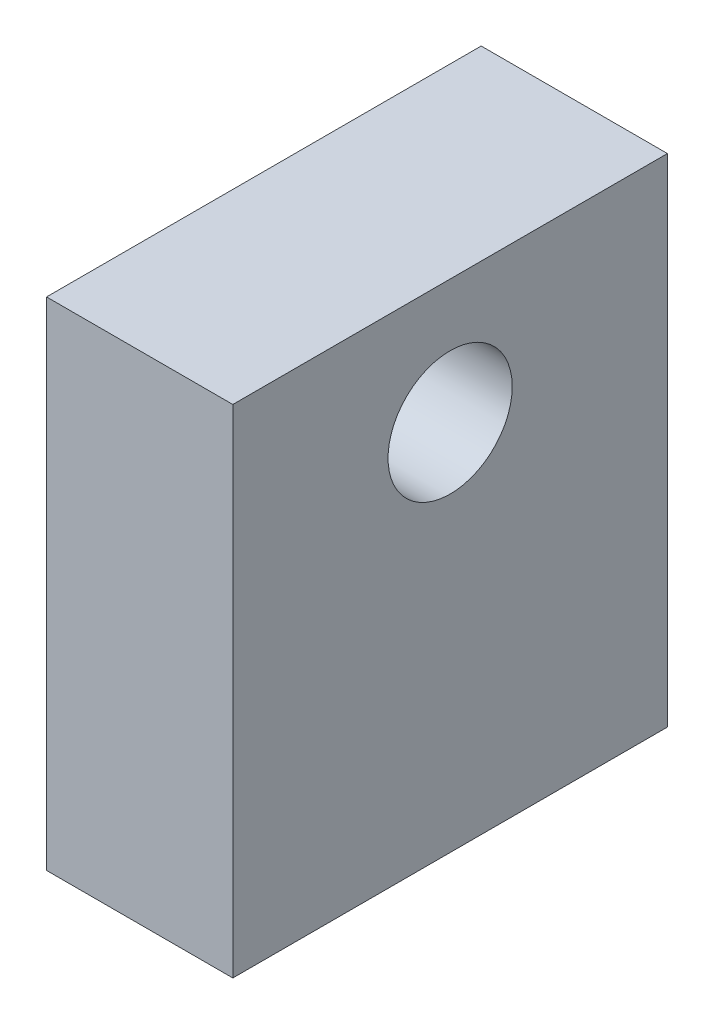
SolidWorks part; units mm, degrees
material "Pine"
ref_plane "Front Plane" through (0, 0, 0) normal (0, 0, 1) x (1, 0, 0)
ref_plane "Top Plane" through (0, 0, 0) normal (0, 1, 0) x (1, 0, 0)
ref_plane "Right Plane" through (0, 0, 0) normal (1, 0, 0) x (0, 0, -1)
sketch "Sketch1" plane through (0, 0, 0) normal (0, 1, 0) x (1, 0, 0)
  line L1 (0, 0) -> (38.1, 0)
  line L2 (0, 0) -> (0, 88.9)
  line L3 (0, 88.9) -> (38.1, 88.9)
  line L4 (38.1, 0) -> (38.1, 88.9)
  dimension "D1" = 38.1
  dimension "D2" = 88.9
extrude "Boss-Extrude1" add sketch "Sketch1" along normal blind 101.6
sketch "Sketch2" plane through (38.1, 0, 0) normal (1, 0, 0) x (0, 0, -1)
  line L0 (0, 101.6) -> (88.9, 101.6) construction
  circle A0 centre (44.45, 76.2) radius 12.7
  dimension "D1" = 25.4
  dimension "D2" = 25.4
extrude "Cut-Extrude1" cut sketch "Sketch2" against normal blind 101.6
